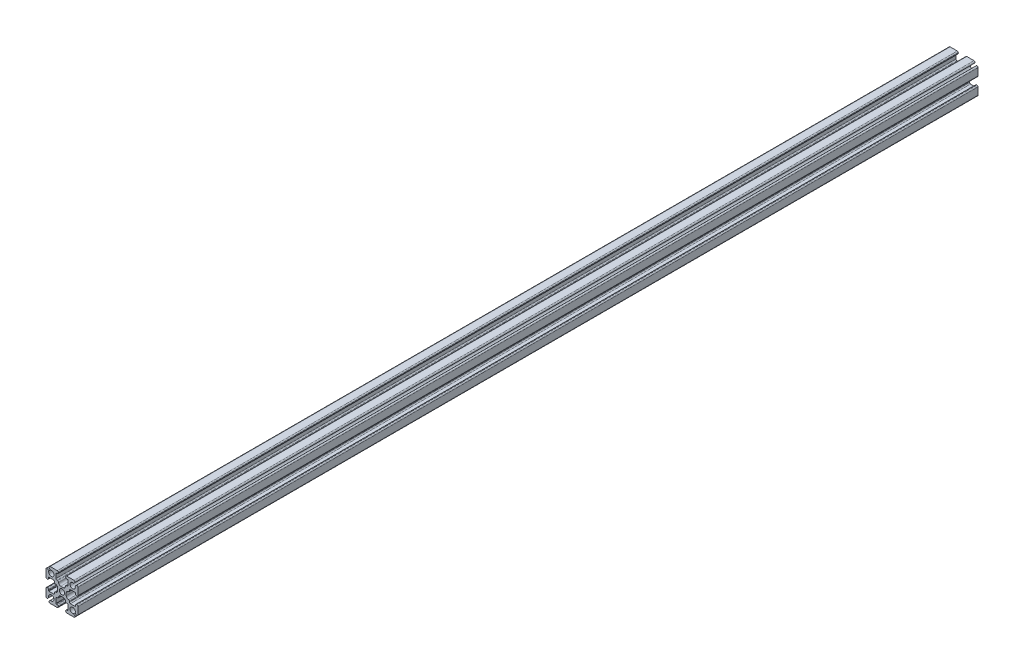
SolidWorks part; units mm, degrees
ref_plane "Front" through (0, 0, 0) normal (0, 0, 1) x (1, 0, 0)
ref_plane "Top" through (0, 0, 0) normal (0, 1, 0) x (1, 0, 0)
ref_plane "Right" through (0, 0, 0) normal (1, 0, 0) x (0, 0, -1)
sketch "Sketch1" plane through (0, 0, 0) normal (0, 0, 1) x (1, 0, 0)
  line L0 (6.6464, 5.9393) -> (6.1636, 5.4565)
  line L1 (5.4565, 6.1636) -> (5.9393, 6.6464)
  line L2 (5.5858, 7.5) -> (2.25, 7.5)
  line L3 (1.75, 7) -> (1.75, 6.8)
  line L4 (2.25, 6.3) -> (2.65, 6.3)
  line L5 (2.85, 6.1) -> (2.85, 4)
  line L6 (2.35, 3.5) -> (2.1, 3.5)
  line L7 (0.6, 2) -> (-0.6, 2)
  line L8 (-2.1, 3.5) -> (-2.35, 3.5)
  line L9 (-2.85, 4) -> (-2.85, 6.1)
  line L10 (-2.65, 6.3) -> (-2.25, 6.3)
  line L11 (-1.75, 6.8) -> (-1.75, 7)
  line L12 (-2.25, 7.5) -> (-5.5858, 7.5)
  line L13 (-5.9393, 6.6464) -> (-5.4565, 6.1636)
  line L14 (-6.1636, 5.4565) -> (-6.6464, 5.9393)
  line L15 (-7.5, 5.5858) -> (-7.5, 2.25)
  line L16 (-7, 1.75) -> (-6.8, 1.75)
  line L17 (-6.3, 2.25) -> (-6.3, 2.65)
  line L18 (-6.1, 2.85) -> (-4, 2.85)
  line L19 (-3.5, 2.35) -> (-3.5, 2.1)
  line L20 (-2, 0.6) -> (-2, -0.6)
  line L21 (-3.5, -2.1) -> (-3.5, -2.35)
  line L22 (-4, -2.85) -> (-6.1, -2.85)
  line L23 (-6.3, -2.65) -> (-6.3, -2.25)
  line L24 (-6.8, -1.75) -> (-7, -1.75)
  line L25 (-7.5, -2.25) -> (-7.5, -5.5858)
  line L26 (-6.6464, -5.9393) -> (-6.1636, -5.4565)
  line L27 (-5.4565, -6.1636) -> (-5.9393, -6.6464)
  line L28 (-5.5858, -7.5) -> (-2.25, -7.5)
  line L29 (-1.75, -7) -> (-1.75, -6.8)
  line L30 (-2.25, -6.3) -> (-2.65, -6.3)
  line L31 (-2.85, -6.1) -> (-2.85, -4)
  line L32 (-2.35, -3.5) -> (-2.1, -3.5)
  line L33 (-0.6, -2) -> (0.6, -2)
  line L34 (2.1, -3.5) -> (2.35, -3.5)
  line L35 (2.85, -4) -> (2.85, -6.1)
  line L36 (2.65, -6.3) -> (2.25, -6.3)
  line L37 (1.75, -6.8) -> (1.75, -7)
  line L38 (2.25, -7.5) -> (5.5858, -7.5)
  line L39 (5.9393, -6.6464) -> (5.4565, -6.1636)
  line L40 (6.1636, -5.4565) -> (6.6464, -5.9393)
  line L41 (7.5, -5.5858) -> (7.5, -2.25)
  line L42 (7, -1.75) -> (6.8, -1.75)
  line L43 (6.3, -2.25) -> (6.3, -2.65)
  line L44 (6.1, -2.85) -> (4, -2.85)
  line L45 (3.5, -2.35) -> (3.5, -2.1)
  line L46 (2, -0.6) -> (2, 0.6)
  line L47 (3.5, 2.1) -> (3.5, 2.35)
  line L48 (4, 2.85) -> (6.1, 2.85)
  line L49 (6.3, 2.65) -> (6.3, 2.25)
  line L50 (6.8, 1.75) -> (7, 1.75)
  line L51 (7.5, 2.25) -> (7.5, 5.5858)
  circle A0 centre (0, 0) radius 1.25
  arc A1 (6.1636, 5.4565) -> (5.4565, 6.1636) centre (5, 5) cw
  arc A2 (5.9393, 6.6464) -> (5.5858, 7.5) centre (5.5858, 7) ccw
  arc A3 (2.25, 7.5) -> (1.75, 7) centre (2.25, 7) ccw
  arc A4 (1.75, 6.8) -> (2.25, 6.3) centre (2.25, 6.8) ccw
  arc A5 (2.65, 6.3) -> (2.85, 6.1) centre (2.65, 6.1) cw
  arc A6 (2.85, 4) -> (2.35, 3.5) centre (2.35, 4) cw
  arc A7 (2.1, 3.5) -> (1.6, 3) centre (2.1, 3) ccw
  arc A8 (1.6, 3) -> (0.6, 2) centre (0.6, 3) cw
  arc A9 (-0.6, 2) -> (-1.6, 3) centre (-0.6, 3) cw
  arc A10 (-1.6, 3) -> (-2.1, 3.5) centre (-2.1, 3) ccw
  arc A11 (-2.35, 3.5) -> (-2.85, 4) centre (-2.35, 4) cw
  arc A12 (-2.85, 6.1) -> (-2.65, 6.3) centre (-2.65, 6.1) cw
  arc A13 (-2.25, 6.3) -> (-1.75, 6.8) centre (-2.25, 6.8) ccw
  arc A14 (-1.75, 7) -> (-2.25, 7.5) centre (-2.25, 7) ccw
  arc A15 (-5.5858, 7.5) -> (-5.9393, 6.6464) centre (-5.5858, 7) ccw
  arc A16 (-5.4565, 6.1636) -> (-6.1636, 5.4565) centre (-5, 5) cw
  arc A17 (-6.6464, 5.9393) -> (-7.5, 5.5858) centre (-7, 5.5858) ccw
  arc A18 (-7.5, 2.25) -> (-7, 1.75) centre (-7, 2.25) ccw
  arc A19 (-6.8, 1.75) -> (-6.3, 2.25) centre (-6.8, 2.25) ccw
  arc A20 (-6.3, 2.65) -> (-6.1, 2.85) centre (-6.1, 2.65) cw
  arc A21 (-4, 2.85) -> (-3.5, 2.35) centre (-4, 2.35) cw
  arc A22 (-3.5, 2.1) -> (-3, 1.6) centre (-3, 2.1) ccw
  arc A23 (-3, 1.6) -> (-2, 0.6) centre (-3, 0.6) cw
  arc A24 (-2, -0.6) -> (-3, -1.6) centre (-3, -0.6) cw
  arc A25 (-3, -1.6) -> (-3.5, -2.1) centre (-3, -2.1) ccw
  arc A26 (-3.5, -2.35) -> (-4, -2.85) centre (-4, -2.35) cw
  arc A27 (-6.1, -2.85) -> (-6.3, -2.65) centre (-6.1, -2.65) cw
  arc A28 (-6.3, -2.25) -> (-6.8, -1.75) centre (-6.8, -2.25) ccw
  arc A29 (-7, -1.75) -> (-7.5, -2.25) centre (-7, -2.25) ccw
  arc A30 (-7.5, -5.5858) -> (-6.6464, -5.9393) centre (-7, -5.5858) ccw
  arc A31 (-6.1636, -5.4565) -> (-5.4565, -6.1636) centre (-5, -5) cw
  arc A32 (-5.9393, -6.6464) -> (-5.5858, -7.5) centre (-5.5858, -7) ccw
  arc A33 (-2.25, -7.5) -> (-1.75, -7) centre (-2.25, -7) ccw
  arc A34 (-1.75, -6.8) -> (-2.25, -6.3) centre (-2.25, -6.8) ccw
  arc A35 (-2.65, -6.3) -> (-2.85, -6.1) centre (-2.65, -6.1) cw
  arc A36 (-2.85, -4) -> (-2.35, -3.5) centre (-2.35, -4) cw
  arc A37 (-2.1, -3.5) -> (-1.6, -3) centre (-2.1, -3) ccw
  arc A38 (-1.6, -3) -> (-0.6, -2) centre (-0.6, -3) cw
  arc A39 (0.6, -2) -> (1.6, -3) centre (0.6, -3) cw
  arc A40 (1.6, -3) -> (2.1, -3.5) centre (2.1, -3) ccw
  arc A41 (2.35, -3.5) -> (2.85, -4) centre (2.35, -4) cw
  arc A42 (2.85, -6.1) -> (2.65, -6.3) centre (2.65, -6.1) cw
  arc A43 (2.25, -6.3) -> (1.75, -6.8) centre (2.25, -6.8) ccw
  arc A44 (1.75, -7) -> (2.25, -7.5) centre (2.25, -7) ccw
  arc A45 (5.5858, -7.5) -> (5.9393, -6.6464) centre (5.5858, -7) ccw
  arc A46 (5.4565, -6.1636) -> (6.1636, -5.4565) centre (5, -5) cw
  arc A47 (6.6464, -5.9393) -> (7.5, -5.5858) centre (7, -5.5858) ccw
  arc A48 (7.5, -2.25) -> (7, -1.75) centre (7, -2.25) ccw
  arc A49 (6.8, -1.75) -> (6.3, -2.25) centre (6.8, -2.25) ccw
  arc A50 (6.3, -2.65) -> (6.1, -2.85) centre (6.1, -2.65) cw
  arc A51 (4, -2.85) -> (3.5, -2.35) centre (4, -2.35) cw
  arc A52 (3.5, -2.1) -> (3, -1.6) centre (3, -2.1) ccw
  arc A53 (3, -1.6) -> (2, -0.6) centre (3, -0.6) cw
  arc A54 (2, 0.6) -> (3, 1.6) centre (3, 0.6) cw
  arc A55 (3, 1.6) -> (3.5, 2.1) centre (3, 2.1) ccw
  arc A56 (3.5, 2.35) -> (4, 2.85) centre (4, 2.35) cw
  arc A57 (6.1, 2.85) -> (6.3, 2.65) centre (6.1, 2.65) cw
  arc A58 (6.3, 2.25) -> (6.8, 1.75) centre (6.8, 2.25) ccw
  arc A59 (7, 1.75) -> (7.5, 2.25) centre (7, 2.25) ccw
  arc A60 (7.5, 5.5858) -> (6.6464, 5.9393) centre (7, 5.5858) ccw
extrude "Boss-Extrude1" add sketch "Sketch1" along normal blind 422.4
